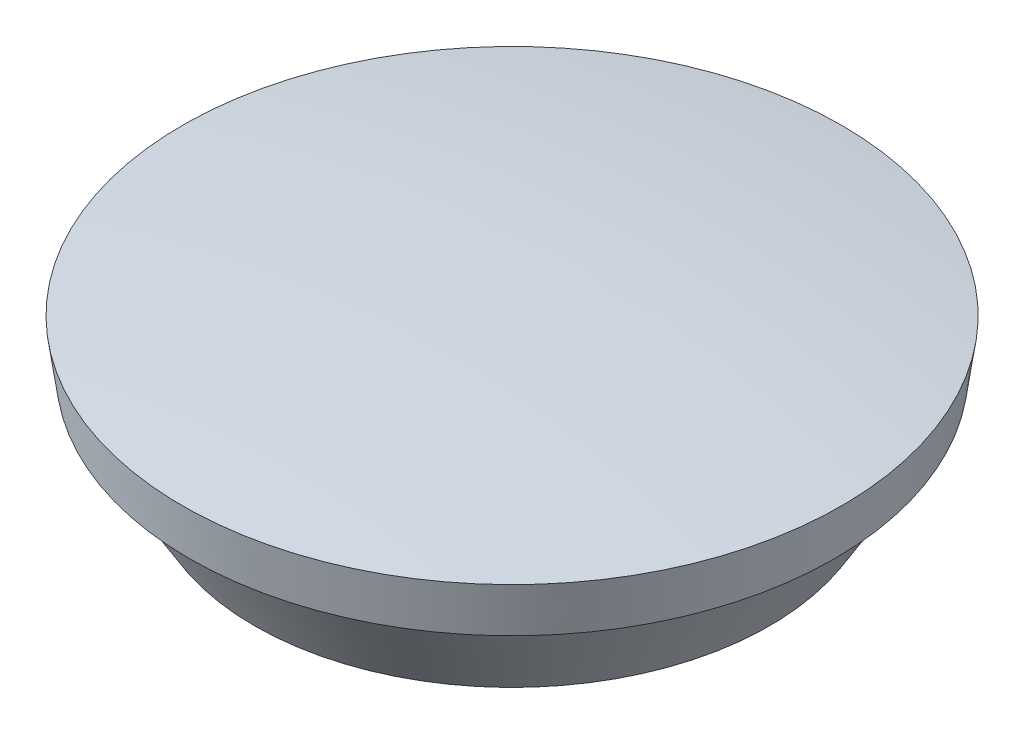
SolidWorks part; units mm, degrees
material "Silicon Rubber"
ref_plane "Front Plane" through (0, 0, 0) normal (0, 0, 1) x (1, 0, 0)
ref_plane "Top Plane" through (0, 0, 0) normal (0, 1, 0) x (1, 0, 0)
ref_plane "Right Plane" through (0, 0, 0) normal (1, 0, 0) x (0, 0, -1)
sketch "Sketch1" plane through (0, 0, 0) normal (1, 0, 0) x (0, 0, -1)
  line L0 (26.0878, 274.978) -> (26.0878, 232.1195)
  line L2 (40.135, 299.274) -> (-40.135, 299.274) construction
  line L5 (0, 324) -> (3.2968, 324)
  line L8 (0, 324) -> (0, 0) construction
  line L9 (26.0878, 262.3641) -> (26.0878, 259.4973) construction
  line L12 (40.135, 302.9291) -> (40.135, 295.6188)
  line L16 (0, 0) -> (51.9362, 327.9125) construction
  line L17 (0, 324) -> (0, 332) construction
  line L18 (26.0878, 274.978) -> (26.0878, 268.978) construction
  line L19 (26.0878, 268.978) -> (26.0878, 248.978) construction
  line L20 (26.0878, 268.978) -> (42.6019, 268.978) construction
  line L21 (26.0878, 274.978) -> (43.5522, 274.978) construction
  line L22 (26.0878, 248.978) -> (39.4342, 248.978) construction
  line L23 (0, 0) -> (-51.9362, 327.9125) construction
  line L24 (-47.4003, 299.274) -> (-47.4003, 268.978) construction
  line L25 (-47.4003, 268.978) -> (-42.6019, 268.978) construction
  line L26 (0, 332) -> (0, 76.96) construction
  line L27 (0, 76.96) -> (400, 76.96) construction
  line L28 (0, 76.96) -> (-400, 76.96) construction
  line L29 (-200, 76.96) -> (-200, 183.96) construction
  line L30 (200, 76.96) -> (200, 183.96) construction
  line L31 (-200, 183.96) -> (-200, 182.57) construction
  line L32 (-200, 182.57) -> (400, 182.57) construction
  line L33 (-200, 182.57) -> (-400, 182.57) construction
  line L38 (0, 186.1152) -> (0, 324)
  line L39 (26.0878, 232.1195) -> (26.0878, 182.57) construction
  line L41 (21.6442, 226.0993) -> (26.0878, 226.0993)
  line L42 (26.0878, 226.0993) -> (26.0878, 186.1152)
  line L43 (26.0878, 186.1152) -> (0, 186.1152)
  line L44 (0, 0) -> (575.122, 0) construction
  arc A0 (-298.7691, 144.7791) -> (305.6579, 129.6043) centre (0, 0) cw construction
  spline S0 degree 3 poles (21.6442, 226.0993) (21.9584, 226.1509) (22.4049, 226.153) (22.896, 226.3321) (23.44, 226.7494) (24.2443, 227.2014) (25.0066, 227.9724) (25.5796, 228.9522) (25.8622, 230.393) (26.0228, 231.4436) (26.0878, 232.1195) knots 0 0 0 0 0.091924 0.112491 0.205673 0.333714 0.459267 0.602423 0.748839 1 1 1 1
  spline S1 degree 3 poles (3.2968, 324) (4.1972, 323.8396) (5.699, 323.816) (7.6935, 323.4297) (9.2722, 323.1563) (10.7507, 322.8538) (12.1816, 322.5577) (13.6372, 322.313) (14.8643, 321.9117) (15.9115, 321.5662) (16.81, 321.2491) (17.7339, 321.0149) (18.8379, 320.6416) (19.931, 320.1935) (21.0686, 319.6948) (22.141, 319.2627) (23.2156, 318.6856) (24.4371, 318.1163) (25.6762, 317.3518) (27.1066, 316.7518) (28.4318, 315.7832) (29.7322, 314.8939) (31.058, 313.93) (32.1959, 312.8581) (33.3378, 311.8503) (34.4539, 310.9646) (35.3895, 309.8867) (36.5078, 309.0949) (37.2942, 308.0208) (38.1233, 307.1238) (38.9048, 306.0961) (39.4724, 304.6349) (40.2774, 303.734) (40.135, 302.9291) knots 0 0 0 0 0.061585 0.100795 0.136831 0.1697 0.202569 0.235438 0.269088 0.289473 0.309858 0.333319 0.353706 0.388423 0.412965 0.437514 0.46634 0.495168 0.528354 0.564387 0.59925 0.638593 0.670824 0.709635 0.743897 0.773612 0.805519 0.839783 0.864953 0.89467 0.922395 0.951224 1 1 1 1
  spline S2 degree 3 poles (40.135, 295.6188) (39.9636, 294.7131) (39.7869, 293.3689) (39.1095, 291.6901) (38.6019, 290.4599) (37.8418, 289.2392) (36.9195, 288.2279) (35.9232, 287.2651) (34.974, 286.2515) (33.8311, 285.3463) (32.8233, 284.2966) (31.8701, 283.2868) (30.7668, 282.4387) (29.8742, 281.4644) (28.8604, 280.5152) (28.0567, 279.5119) (27.1438, 278.5569) (26.4968, 277.0287) (26.0081, 275.8567) (26.0878, 274.978) knots 0 0 0 0 0.108356 0.15601 0.210945 0.263562 0.322855 0.370186 0.4254 0.484692 0.539909 0.595126 0.646549 0.701764 0.749093 0.808384 0.85195 0.901837 1 1 1 1
  point P10 (0, 299.274)
  point P63 (0, 299.274)
  dimension "D3" = 9
  dimension "D1" = 40.135
  dimension "D2" = 324
  dimension "D4" = 8
  dimension "D5" = 3.2968
  dimension "D6" = 4.4435
  dimension "D7" = 6.0202
  dimension "D8" = 7.7403
  dimension "D9" = 6
  dimension "D10" = 20
  dimension "D11" = 9.317
  dimension "D12" = 10.7504
  dimension "D13" = 255.04
  dimension "D14" = 107
  dimension "D15" = 107
  dimension "D16" = 332
  dimension "D17" = 105.61
  dimension "D18" = 105.61
  dimension "D19" = 12.1838
  dimension "D20" = 13.6172
  dimension "D21" = 15.0506
  dimension "D22" = 15.9106
  dimension "D23" = 16.7707
  dimension "D24" = 17.7739
  dimension "D25" = 18.6341
  dimension "D26" = 20.0676
  dimension "D27" = 21.0708
  dimension "D28" = 22.0743
  dimension "D29" = 23.2209
  dimension "D30" = 24.3677
  dimension "D31" = 25.6578
  dimension "D32" = 27.0911
  dimension "D33" = 28.3811
  dimension "D34" = 29.8146
  dimension "D35" = 30.9613
  dimension "D36" = 32.2513
  dimension "D37" = 33.3981
  dimension "D38" = 34.4014
  dimension "D39" = 35.4048
  dimension "D40" = 36.5516
  dimension "D41" = 37.2681
  dimension "D42" = 38.1282
  dimension "D43" = 38.8449
  dimension "D44" = 39.4183
  dimension "D45" = 39.9917
  dimension "D46" = 323.8567
  dimension "D47" = 323.7133
  dimension "D48" = 323.4267
  dimension "D49" = 323.1399
  dimension "D50" = 322.8533
  dimension "D51" = 322.5666
  dimension "D52" = 322.2799
  dimension "D53" = 321.8499
  dimension "D54" = 321.5632
  dimension "D55" = 321.2765
  dimension "D56" = 320.9899
  dimension "D57" = 320.7031
  dimension "D58" = 320.1297
  dimension "D59" = 319.6998
  dimension "D60" = 319.2698
  dimension "D61" = 318.6965
  dimension "D62" = 318.1231
  dimension "D63" = 317.4064
  dimension "D64" = 316.6897
  dimension "D65" = 315.8296
  dimension "D66" = 314.8263
  dimension "D67" = 313.9663
  dimension "D68" = 312.8195
  dimension "D69" = 311.8162
  dimension "D70" = 310.9562
  dimension "D71" = 309.9528
  dimension "D72" = 308.9493
  dimension "D73" = 308.0893
  dimension "D74" = 307.086
  dimension "D75" = 306.0826
  dimension "D76" = 304.9359
  dimension "D77" = 303.9325
  dimension "D78" = 302.9291
sketch "Sketch2" plane through (0, 0, 0) normal (1, 0, 0) x (0, 0, -1)
  line L0 (0, 324) -> (3.2968, 324) construction
  line L1 (26.5078, 274.997) -> (26.5078, 273.8486)
  line L2 (40.5477, 295.5407) -> (40.5477, 314.2386)
  line L3 (40.135, 295.6188) -> (40.135, 302.9302) construction
  line L4 (40.135, 295.6188) -> (26.0878, 274.978) construction
  line L5 (0, 324.42) -> (3.4084, 324.42) construction
  line L6 (3.2968, 324) -> (40.135, 302.9302) construction
  line L7 (3.4084, 324.42) -> (40.555, 303.1738) construction
  line L8 (26.0878, 274.978) -> (26.0878, 232.1195) construction
  line L9 (40.555, 295.4895) -> (26.435, 274.7417) construction
  line L10 (0, 5) -> (0, 407.9498) construction
  line L12 (26.5078, 273.8486) -> (38.5078, 273.8486) construction
  line L13 (26.5078, 274.997) -> (26.5078, 232.1195) construction
  line L14 (38.5078, 273.8486) -> (45.76, 323.5611) construction
  line L17 (40.5477, 314.2386) -> (45.93, 323.5611) construction
  line L18 (45.93, 323.5611) -> (45.76, 323.5611) construction
  line L19 (0, 186.1152) -> (0, 324) construction
  line L20 (0, 324) -> (0, 332) construction
  line L21 (40.555, 295.4895) -> (40.555, 303.1738) construction
  line L22 (0, 5) -> (47.1644, 328.2999) construction
  line L23 (45.93, 323.5611) -> (46.473, 323.5611) construction
  line L24 (46.473, 323.5611) -> (39.2208, 273.8486) construction
  line L25 (39.2208, 273.8486) -> (26.5078, 273.8486)
  line L26 (44.7753, 321.5611) -> (46.1813, 321.5611)
  line L27 (44.7753, 321.5611) -> (40.5477, 314.2386)
  line L28 (46.1813, 321.5611) -> (39.2208, 273.8486)
  spline S0 degree 1 poles (40.5477, 295.5407) (26.5078, 274.997) knots 0 0 1 1 construction
  spline S1 degree 3 poles (40.135, 295.6188) (39.9636, 294.7131) (39.7869, 293.3689) (39.1095, 291.6901) (38.6019, 290.4599) (37.8418, 289.2392) (36.9195, 288.2279) (35.9232, 287.2651) (34.974, 286.2515) (33.8311, 285.3463) (32.8233, 284.2966) (31.8701, 283.2868) (30.7668, 282.4387) (29.8742, 281.4644) (28.8604, 280.5152) (28.0567, 279.5119) (27.1438, 278.5569) (26.4968, 277.0287) (26.0081, 275.8567) (26.0878, 274.978) knots 0 0 0 0 0.108356 0.15601 0.210945 0.263562 0.322855 0.370186 0.4254 0.484692 0.539909 0.595126 0.646549 0.701764 0.749093 0.808384 0.85195 0.901837 1 1 1 1 construction
  spline S2 degree 3 poles (40.5477, 295.5407) (40.4477, 295.0127) (40.2928, 293.9708) (39.9309, 292.5875) (39.5162, 291.5815) (39.1084, 290.578) (38.4397, 289.317) (37.3314, 288.0326) (36.3684, 287.1154) (35.6302, 286.3401) (35.0165, 285.7627) (34.3943, 285.2472) (33.6355, 284.5566) (32.9204, 283.7714) (32.1297, 282.9861) (31.4852, 282.4595) (30.915, 281.9635) (30.3717, 281.3913) (29.7828, 280.8046) (29.2276, 280.2622) (28.7248, 279.6749) (28.1804, 279.0397) (27.6518, 278.4702) (27.3081, 277.8768) (26.9952, 277.1272) (26.598, 276.1645) (26.4648, 275.4705) (26.5078, 274.997) knots 0 0 0 0 0.062544 0.125088 0.15636 0.187632 0.250176 0.31272 0.375264 0.406536 0.437808 0.46908 0.500352 0.562896 0.594168 0.62544 0.656713 0.687985 0.719257 0.750529 0.781801 0.813073 0.844345 0.875617 0.906889 0.938161 1.000705 1.000705 1.000705 1.000705
  point P38 (0, 328)
  dimension "D4" = 1.1484
  dimension "D5" = 8.3
  dimension "D6" = 30
  dimension "D7" = 45.93
  dimension "D8" = 40.39
  dimension "D9" = 8.3
  dimension "D10" = 40.5477
  dimension "D3" = 12
  dimension "D11" = 18.6979
  dimension "D12" = 2
  dimension "D13" = 5
  dimension "D1" = 0.42
  dimension "D2" = 0.42
revolve "Revolve6" [suppressed] add sketch "Sketch2" angle 360 about L10
sketch "Sketch3" [suppressed] plane through (0, 0, 0) normal (1, 0, 0) x (0, 0, -1)
  line L0 (44.1979, 321.5611) -> (40.5477, 314.2386) construction
  line L3 (46.1813, 321.5611) -> (-46.1813, 321.5611) construction
  line L4 (44.7753, 321.5611) -> (-44.7753, 321.5611) construction
  line L5 (40.5477, 314.2386) -> (-40.5477, 314.2386) construction
  line L6 (40.5477, 314.2386) -> (54.812, 333.8718)
  line L8 (54.812, 333.8718) -> (54.812, 347.837)
  line L9 (54.812, 347.837) -> (0, 347.837)
  line L10 (0, 347.837) -> (0, 311.6751)
  line L11 (0, 186.1152) -> (0, 324) construction
  line L12 (0, 311.6751) -> (40.5477, 311.6751)
  line L13 (40.5477, 311.6751) -> (40.5477, 314.2386)
  dimension "D1" = 36
  dimension "D2" = 54.812
revolve "Cut-Revolve1" [suppressed] cut sketch "Sketch3" angle 360 about L10
sketch "Sketch4" [suppressed] plane through (0, 273.8486, 0) normal (0, -1, 0) x (1, 0, 0)
  line L0 (0, 0) -> (36, 0) construction
  line L1 (0, 0) -> (-31.1769, 18) construction
  circle A0 centre (0, 0) radius 36 construction
  circle A1 centre (-31.1769, 18) radius 3
  circle A2 centre (36, 0) radius 3
  dimension "D1" = 72
  dimension "D3" = 6
  dimension "D4" = 6
  dimension "D2" = 150
extrude "Boss-Extrude1" [suppressed] add sketch "Sketch4" along normal blind 2
sketch "Sketch5" [suppressed] plane through (0, 263.8486, 0) normal (0, -1, 0) x (1, 0, 0)
  circle A0 centre (36, 0) radius 3.175
  circle A1 centre (-31.1769, 18) radius 3.175
  dimension "D1" = 6.35
  dimension "D2" = 6.35
extrude "Boss-Extrude2" [suppressed] add sketch "Sketch5" along normal blind 5
chamfer "Chamfer2" [suppressed] distance 9 angle 4
sketch "Sketch7" plane through (0, 0, 0) normal (1, 0, 0) x (0, 0, -1)
  line L0 (0, 5) -> (0, 407.9498) construction
  line L1 (26.5078, 273.8486) -> (39.2208, 273.8486) construction
  line L2 (39.2208, 273.8486) -> (39.2208, 272.3194)
  line L4 (26.5078, 273.8486) -> (26.5078, 274.3486)
  line L5 (26.5078, 274.3486) -> (39.2208, 274.3486)
  line L6 (39.2208, 274.3486) -> (39.2208, 273.8486)
  circle A0 centre (0, -0.122) radius 275.25 construction
  arc A1 (39.2208, 272.3194) -> (26.5078, 273.8486) centre (0, -0.122) ccw
  dimension "D1" = 550.5
  dimension "D2" = 0.5
revolve "Revolve7" [suppressed] add sketch "Sketch7" angle 360 about L10
sketch "Sketch9" [suppressed] plane through (0, 271.8486, 0) normal (0, -1, 0) x (1, 0, 0)
  circle A0 centre (36, 0) radius 1.5
  circle A1 centre (-31.1769, 18) radius 1.5
  dimension "D1" = 3
  dimension "D2" = 3
extrude "Cut-Extrude1" [suppressed] cut sketch "Sketch9" against normal blind 6
sketch "Sketch10" [suppressed] plane through (0, 271.8486, 0) normal (0, -1, 0) x (1, 0, 0)
  circle A0 centre (36, 0) radius 2
  circle A1 centre (-31.1769, 18) radius 2
  dimension "D1" = 4
  dimension "D2" = 4
extrude "Cut-Extrude2" [suppressed] cut sketch "Sketch10" against normal blind 0.5
chamfer "Chamfer3" [suppressed] distance 0.55 angle 45
sketch "Sketch11" plane through (0, 0, 0) normal (1, 0, 0) x (0, 0, -1)
  line L0 (46.1813, 321.5611) -> (44.7753, 321.5611)
  line L1 (44.7753, 321.5611) -> (36.8783, 308.577)
  line L2 (46.1813, 321.5611) -> (47.1962, 328.6282)
  line L3 (0, 332) -> (0, 324)
  arc A0 (305.6579, 129.6043) -> (-298.7691, 144.7791) centre (0, 0) ccw construction
  arc A1 (47.1962, 328.6282) -> (0, 332) centre (0, 0) ccw
  arc A2 (36.8783, 308.577) -> (0, 324) centre (0.7725, 274.0456) ccw
  spline S0 degree 3 poles (3.2968, 324) (4.1972, 323.8396) (5.699, 323.816) (7.6935, 323.4297) (9.2722, 323.1563) (10.7507, 322.8538) (12.1816, 322.5577) (13.6372, 322.313) (14.8643, 321.9117) (15.9115, 321.5662) (16.81, 321.2491) (17.7339, 321.0149) (18.8379, 320.6416) (19.931, 320.1935) (21.0686, 319.6948) (22.141, 319.2627) (23.2156, 318.6856) (24.4371, 318.1163) (25.6762, 317.3518) (27.1066, 316.7518) (28.4318, 315.7832) (29.7322, 314.8939) (31.058, 313.93) (32.1959, 312.8581) (33.3378, 311.8503) (34.4539, 310.9646) (35.3895, 309.8867) (36.5078, 309.0949) (37.2942, 308.0208) (38.1233, 307.1238) (38.9048, 306.0961) (39.4724, 304.6349) (40.2774, 303.734) (40.135, 302.9291) knots 0 0 0 0 0.061585 0.100795 0.136831 0.1697 0.202569 0.235438 0.269088 0.289473 0.309858 0.333319 0.353706 0.388423 0.412965 0.437514 0.46634 0.495168 0.528354 0.564387 0.59925 0.638593 0.670824 0.709635 0.743897 0.773612 0.805519 0.839783 0.864953 0.89467 0.922395 0.951224 1 1 1 1 construction
  dimension "D1" = 332
  dimension "D2" = 49.9604
  dimension "D3" = 98.173
revolve "Revolve8" add sketch "Sketch11" angle 360 about L10
